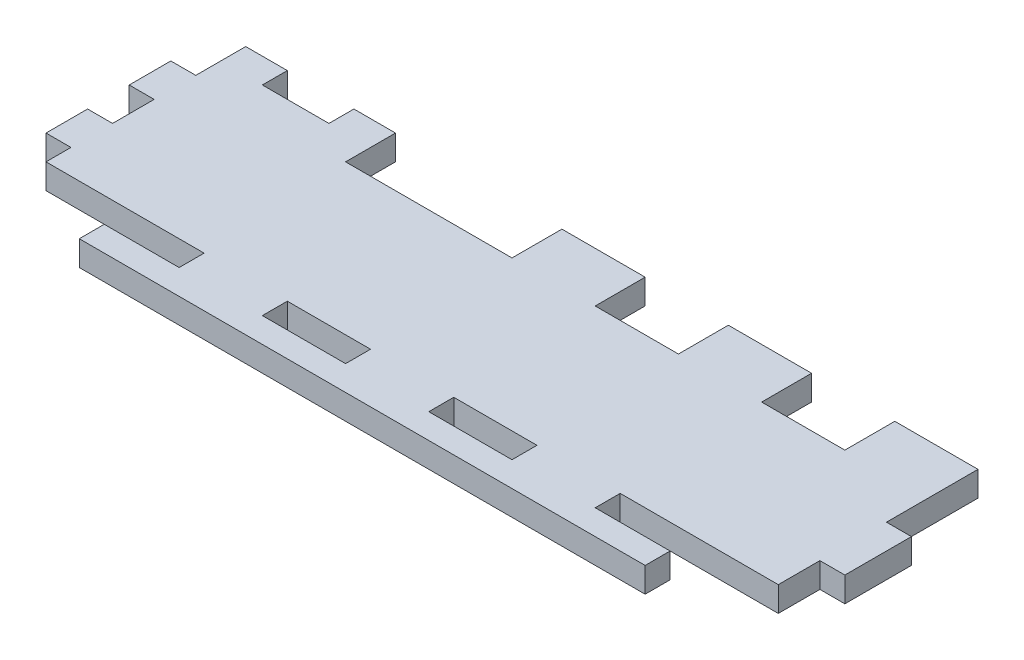
SolidWorks part; units mm, degrees
material "Maple"
ref_plane "Front Plane" through (0, 0, 0) normal (0, 0, 1) x (1, 0, 0)
ref_plane "Top Plane" through (0, 0, 0) normal (0, 1, 0) x (1, 0, 0)
ref_plane "Right Plane" through (0, 0, 0) normal (1, 0, 0) x (0, 0, -1)
sketch "Sketch1" plane through (0, 0, 0) normal (0, 1, 0) x (1, 0, 0)
  line L1 (0, 0) -> (88, 0)
  line L2 (0, 0) -> (0, -18)
  line L3 (0, -18) -> (88, -18)
  line L4 (88, 0) -> (88, -18)
  dimension "D1" = 88
  dimension "D2" = 18
extrude "Boss-Extrude1" add sketch "Sketch1" along normal blind 3
sketch "Sketch2" plane through (0, 0, 0) normal (0, -1, 0) x (1, 0, 0)
  line L0 (88, 0) -> (0, 0) construction
  line L1 (0, 0) -> (18, 0)
  line L2 (0, 0) -> (0, -3)
  line L3 (0, -3) -> (18, -3)
  line L4 (18, 0) -> (18, -3)
  line L5 (0, 0) -> (0, 18) construction
  dimension "D1" = 18
  dimension "D2" = 3
extrude "Boss-Extrude2" add sketch "Sketch2" against normal through all
sketch "Sketch3" plane through (0, 0, 0) normal (0, -1, 0) x (1, 0, 0)
  line L0 (44, 18) -> (44, 0) construction
  line L1 (0, 18) -> (88, 18) construction
  line L2 (88, 0) -> (18, 0) construction
  line L4 (39, 21) -> (49, 21)
  line L5 (39, 21) -> (39, 18)
  line L6 (39, 18) -> (49, 18)
  line L7 (49, 21) -> (49, 18)
  line L8 (39, 21) -> (49, 18) construction
  line L9 (39, 18) -> (49, 21) construction
  point P6 (44, 19.5)
  dimension "D1" = 3
  dimension "D2" = 10
extrude "Boss-Extrude3" add sketch "Sketch3" against normal through all
pattern_linear "LPattern1" count 3 spacing 20 along (1, 0, 0) count 3 spacing 20 along (-1, 0, 0) of "Boss-Extrude3"
sketch "Sketch4" plane through (0, 0, 0) normal (0, -1, 0) x (-1, 0, 0)
  line L1 (1, -21) -> (0, -21)
  line L2 (1, -21) -> (1, -18)
  line L3 (1, -18) -> (0, -18)
  line L4 (0, -21) -> (0, -18)
  line L5 (-89, -21) -> (-88, -21)
  line L6 (-89, -21) -> (-89, -18)
  line L7 (-89, -18) -> (-88, -18)
  line L8 (-88, -21) -> (-88, -18)
extrude "Cut-Extrude1" cut sketch "Sketch4" against normal through all
sketch "Sketch5" plane through (0, 0, 0) normal (0, -1, 0) x (-1, 0, 0)
  line L0 (-88, -21) -> (-88, 0) construction
  line L1 (0, -21) -> (-88, -21)
  line L2 (0, -21) -> (0, -24)
  line L3 (0, -24) -> (-88, -24)
  line L4 (-88, -21) -> (-88, -24)
  dimension "D1" = 3
extrude "Boss-Extrude4" add sketch "Sketch5" against normal through all
sketch "Sketch6" plane through (0, 0, 0) normal (0, -1, 0) x (-1, 0, 0)
  line L0 (0, 3) -> (-18, 3) construction
  line L1 (0, 3) -> (-5, 3)
  line L2 (0, 3) -> (0, 6)
  line L3 (0, 6) -> (-5, 6)
  line L4 (-5, 3) -> (-5, 6)
  line L5 (-18, 3) -> (-13, 3)
  line L6 (-18, 3) -> (-18, 6)
  line L7 (-18, 6) -> (-13, 6)
  line L8 (-13, 3) -> (-13, 6)
  dimension "D1" = 3
  dimension "D2" = 5
extrude "Boss-Extrude5" add sketch "Sketch6" against normal through all
sketch "Sketch7" plane through (0, 0, 0) normal (0, -1, 0) x (-1, 0, 0)
  line L0 (-88, 0) -> (-18, 0) construction
  line L1 (-88, 0) -> (-78, 0)
  line L2 (-88, 0) -> (-88, 6)
  line L3 (-88, 6) -> (-78, 6)
  line L4 (-78, 0) -> (-78, 6)
  dimension "D1" = 6
  dimension "D2" = 10
extrude "Boss-Extrude6" add sketch "Sketch7" against normal through all
pattern_linear "LPattern2" count 3 spacing 20 along (-1, 0, 0) of "Boss-Extrude6"
sketch "Sketch9" plane through (0, 0, 0) normal (0, -1, 0) x (-1, 0, 0)
  line L0 (0, 6) -> (0, -24) construction
  line L1 (-9, -21) -> (0, -21)
  line L2 (-9, -21) -> (-9, -18)
  line L3 (-9, -18) -> (0, -18)
  line L4 (0, -21) -> (0, -18)
  line L5 (-88, -24) -> (-88, 6) construction
  line L6 (-79, -21) -> (-88, -21)
  line L7 (-79, -21) -> (-79, -18)
  line L8 (-79, -18) -> (-88, -18)
  line L9 (-88, -21) -> (-88, -18)
  line L10 (-69, -18) -> (-79, -18) construction
  line L11 (-9, -18) -> (-19, -18) construction
extrude "Cut-Extrude2" cut sketch "Sketch9" against normal through all
sketch "Sketch10" plane through (0, 0, 0) normal (0, -1, 0) x (-1, 0, 0)
  line L0 (0, 6) -> (0, -18) construction
  line L1 (0, -15) -> (3, -15)
  line L2 (0, -15) -> (0, -10)
  line L3 (0, -10) -> (3, -10)
  line L4 (3, -15) -> (3, -10)
  line L10 (0, -18) -> (-19, -18) construction
  line L11 (-88, -18) -> (-88, 6) construction
  line L12 (-88, -13) -> (-91, -13)
  line L13 (-88, -13) -> (-88, -5)
  line L14 (-88, -5) -> (-91, -5)
  line L15 (-91, -13) -> (-91, -5)
  line L16 (-69, -18) -> (-88, -18) construction
  line L17 (-78, 0) -> (-68, 0) construction
  line L19 (0, -5) -> (3, -5)
  line L20 (0, -5) -> (0, 0)
  line L21 (0, 0) -> (3, 0)
  line L22 (3, -5) -> (3, 0)
  dimension "D1" = 3
  dimension "D2" = 3
  dimension "D3" = 5
  dimension "D4" = 3
  dimension "D5" = 5
  dimension "D6" = 5
  dimension "D7" = 5
extrude "Boss-Extrude8" add sketch "Sketch10" against normal through all
sketch "Sketch11" plane through (0, 0, 0) normal (0, -1, 0) x (-1, 0, 0)
  line L0 (0, -21) -> (-19, -21) construction
  line L1 (0, -24) -> (-10, -24)
  line L2 (0, -24) -> (0, -21)
  line L3 (0, -21) -> (-10, -21)
  line L4 (-10, -24) -> (-10, -21)
  line L5 (-69, -21) -> (-88, -21) construction
  line L6 (-88, -24) -> (-78, -24)
  line L7 (-88, -24) -> (-88, -21)
  line L8 (-88, -21) -> (-78, -21)
  line L9 (-78, -24) -> (-78, -21)
  dimension "D1" = 10
  dimension "D2" = 10
extrude "Cut-Extrude3" cut sketch "Sketch11" against normal through all
equation "\"D2@Sketch11\"=\"D1@Sketch11\""
